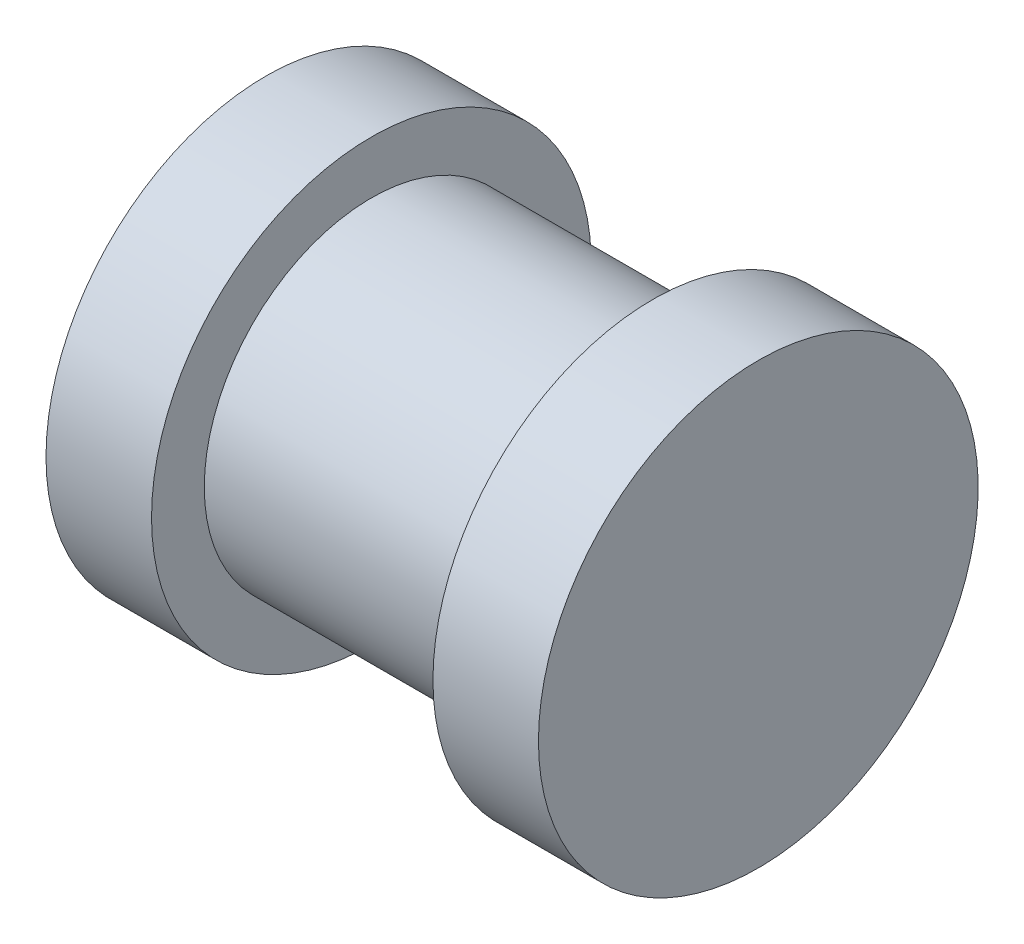
SolidWorks part; units mm, degrees
ref_plane "Front Plane" through (0, 0, 0) normal (0, 0, 1) x (1, 0, 0)
ref_plane "Top Plane" through (0, 0, 0) normal (0, 1, 0) x (1, 0, 0)
ref_plane "Right Plane" through (0, 0, 0) normal (1, 0, 0) x (0, 0, -1)
sketch "Sketch1" plane through (0, 0, 0) normal (0, 0, 1) x (1, 0, 0)
  line L0 (0, 0) -> (14.224, 0) construction
  line L1 (14.224, 0) -> (14.224, 6.35)
  line L2 (14.224, 6.35) -> (11.176, 6.35)
  line L3 (11.176, 6.35) -> (11.176, 4.826)
  line L4 (11.176, 4.826) -> (3.048, 4.826)
  line L5 (3.048, 4.826) -> (3.048, 6.35)
  line L6 (3.048, 6.35) -> (0, 6.35)
  line L7 (0, 6.35) -> (0, 0)
  line L8 (0, 0) -> (14.224, 0)
  dimension "D1" = 14.224
  dimension "D2" = 3.048
  dimension "D3" = 12.7
  dimension "D4" = 9.652
revolve "Revolve1" add sketch "Sketch1" angle 360 about L0
